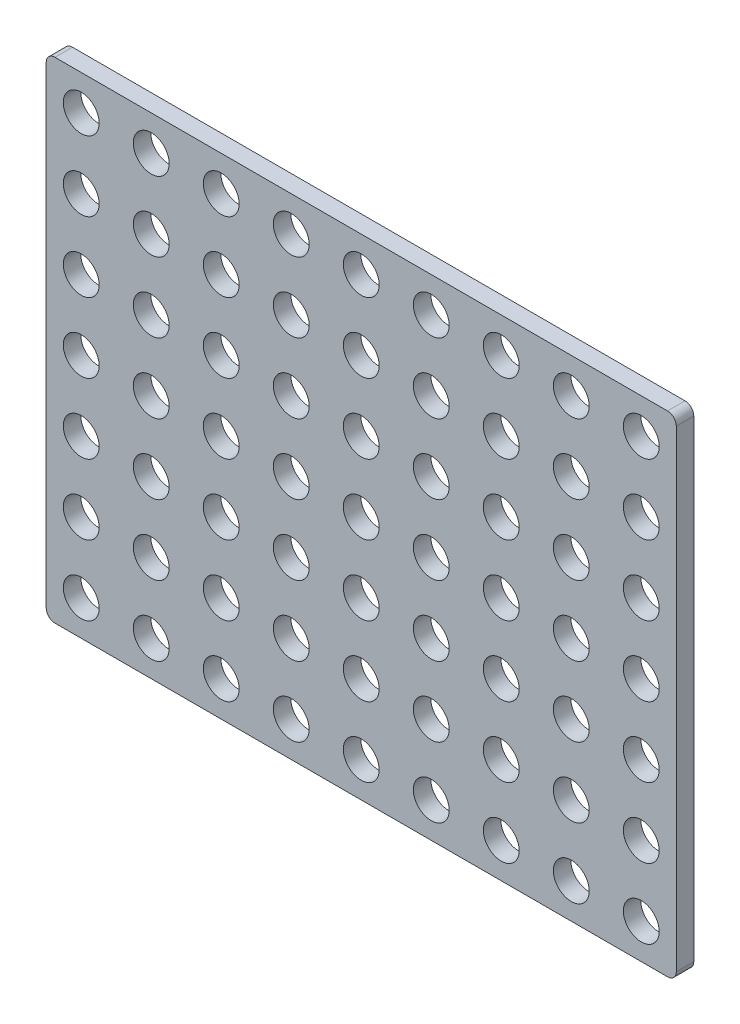
SolidWorks part; units mm, degrees
ref_plane "Front Plane" through (0, 0, 0) normal (0, 0, 1) x (1, 0, 0)
ref_plane "Top Plane" through (0, 0, 0) normal (0, 1, 0) x (1, 0, 0)
ref_plane "Right Plane" through (0, 0, 0) normal (1, 0, 0) x (0, 0, -1)
sketch "Sketch1" plane through (0, 0, 0) normal (0, 0, 1) x (1, 0, 0)
  line L1 (0, 0) -> (72, 0)
  line L2 (0, 0) -> (0, 56)
  line L3 (0, 56) -> (72, 56)
  line L4 (72, 0) -> (72, 56)
  dimension "PlateHeight" = 56
  dimension "PlateWidth" = 72
extrude "Boss-Extrude1" add sketch "Sketch1" along normal blind 2
hole_wizard "Ø4.1 (4.1) Diameter Hole1" positions "Sketch3" profile "Sketch2" hole size "Ø4.1" standard "ANSI Metric" end condition through all
sketch "Sketch3" plane through (0, 0, 2) normal (0, 0, 1) x (1, 0, 0)
  point P0 (4, 4)
sketch "Sketch2" plane through (4, 4, 2) normal (1, 0, 0) x (0, -1, 0)
  line L0 (0, 0) -> (0, 2)
  line L1 (0, 2) -> (2.05, 2)
  line L2 (2.05, 2) -> (2.05, 0)
  line L5 (2.05, 0) -> (0, 0)
  line L11 (0, -6.35) -> (0, 107.95) construction
  dimension "Thru Hole Dia." = 4.1
  dimension "Thru Hole Depth" = 2
pattern_linear "LPattern1" count 7 spacing 8 along (0, 1, 0) count 9 spacing 8 along (1, 0, 0) of "Ø4.1 (4.1) Diameter Hole1"
fillet "Fillet1" radius 1 4 edges at (0, 0, 1) (72, 0, 1) (72, 56, 1) (0, 56, 1)
